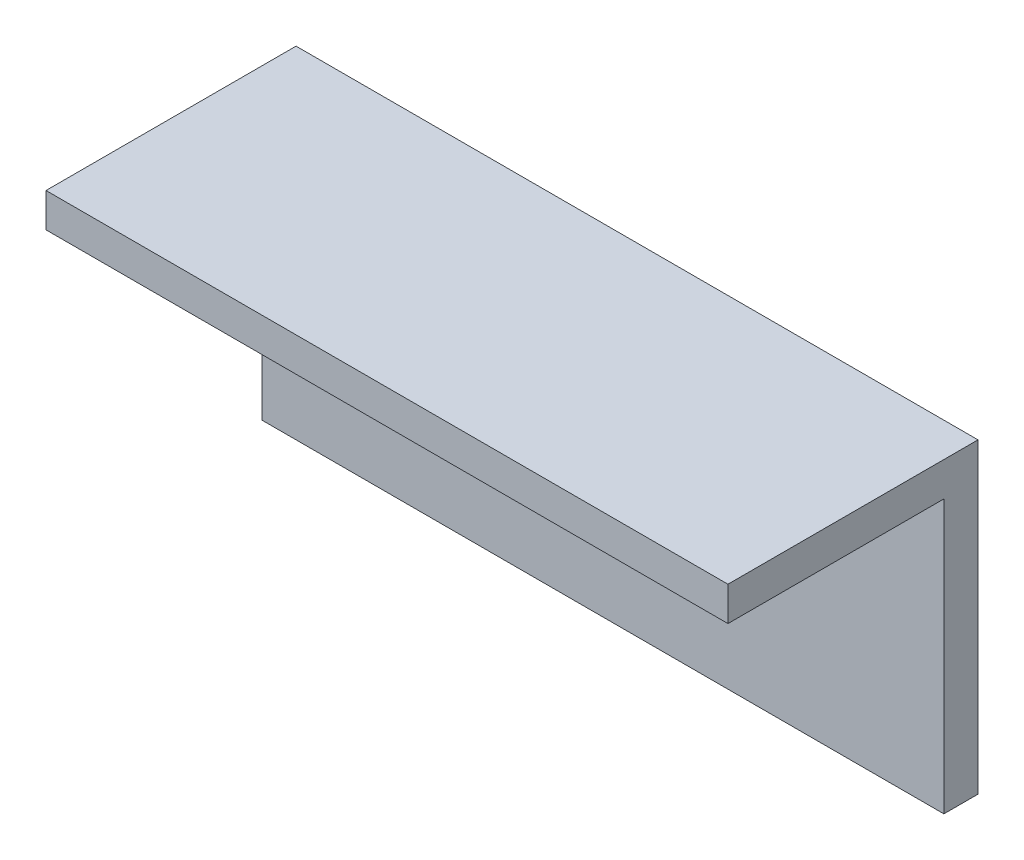
SolidWorks part; units mm, degrees
ref_plane "정면" through (0, 0, 0) normal (0, 0, 1) x (1, 0, 0)
ref_plane "윗면" through (0, 0, 0) normal (0, 1, 0) x (1, 0, 0)
ref_plane "우측면" through (0, 0, 0) normal (1, 0, 0) x (0, 0, -1)
sketch "스케치1" plane through (0, 0, 0) normal (0, 0, 1) x (1, 0, 0)
  line L1 (-30, 13.5) -> (30, 13.5)
  line L2 (-30, 13.5) -> (-30, -13.5)
  line L3 (-30, -13.5) -> (30, -13.5)
  line L4 (30, 13.5) -> (30, -13.5)
  line L5 (-30, 13.5) -> (30, -13.5) construction
  line L6 (-30, -13.5) -> (30, 13.5) construction
  point P0 (0, 0)
  dimension "D1" = 27
  dimension "D2" = 60
extrude "보스-돌출1" add sketch "스케치1" along normal blind 3
sketch "스케치2" plane through (0, 0, 3) normal (0, 0, 1) x (1, 0, 0)
  line L0 (30, -13.5) -> (30, 13.5) construction
  line L1 (-30, 13.5) -> (30, 13.5)
  line L2 (-30, 13.5) -> (-30, 10.5)
  line L3 (-30, 10.5) -> (30, 10.5)
  line L4 (30, 13.5) -> (30, 10.5)
  dimension "D1" = 3
extrude "보스-돌출2" add sketch "스케치2" along normal blind 19
